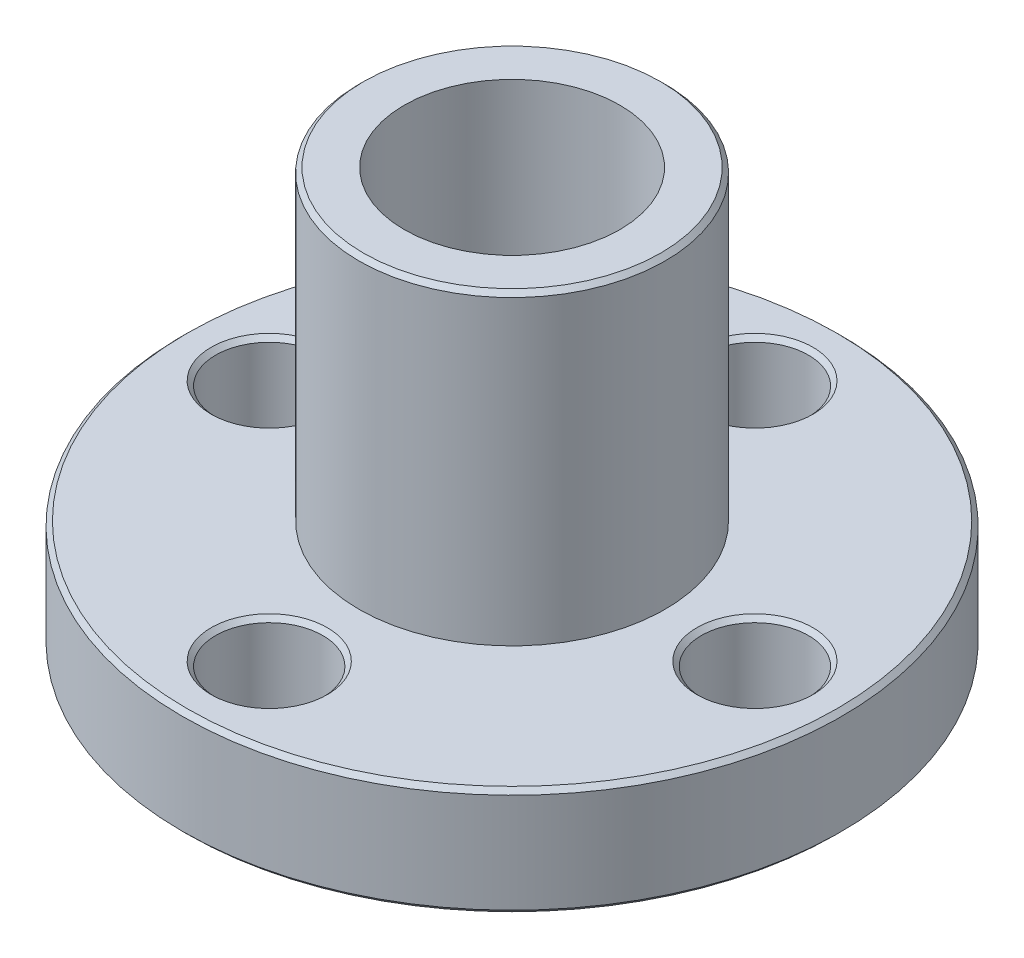
SolidWorks part; units mm, degrees
ref_plane "Alzado" through (0, 0, 0) normal (0, 0, 1) x (1, 0, 0)
ref_plane "Planta" through (0, 0, 0) normal (0, 1, 0) x (1, 0, 0)
ref_plane "Vista lateral" through (0, 0, 0) normal (1, 0, 0) x (0, 0, -1)
sketch "Croquis1" plane through (0, 0, 0) normal (0, 1, 0) x (1, 0, 0)
  circle A0 centre (0, 0) radius 10.925
  dimension "D1" = 21.85
extrude "Saliente-Extruir1" add sketch "Croquis1" along normal blind 3.6
sketch "Croquis2" plane through (0, 3.6, 0) normal (0, 1, 0) x (1, 0, 0)
  line L0 (-8.05, 0) -> (8.05, 0) construction
  line L1 (0, 8.05) -> (0, -8.05) construction
  circle A0 centre (-8.05, 0) radius 1.775
  circle A1 centre (8.05, 0) radius 1.775
  circle A2 centre (0, -8.05) radius 1.775
  circle A3 centre (0, 8.05) radius 1.775
  point P2 (0, 0)
  point P7 (0, 0)
  dimension "D2" = 3.55
  dimension "D1" = 16.1
extrude "Cortar-Extruir1" cut sketch "Croquis2" against normal blind 3.6
sketch "Croquis3" plane through (0, 3.6, 0) normal (0, 1, 0) x (1, 0, 0)
  circle A0 centre (0, 0) radius 5.075
  dimension "D1" = 10.15
extrude "Saliente-Extruir2" add sketch "Croquis3" along normal blind 10.15
sketch "Croquis4" plane through (0, 0, 0) normal (0, -1, 0) x (1, 0, 0)
  circle A0 centre (0, 0) radius 5.075
  dimension "D1" = 10.15
extrude "Saliente-Extruir3" add sketch "Croquis4" along normal blind 1.5
sketch "Croquis5" plane through (0, -1.5, 0) normal (0, -1, 0) x (1, 0, 0)
  circle A0 centre (0, 0) radius 3.575
  circle A1 centre (0, 0) radius 5.075 construction
  dimension "D1" = 1.5
extrude "Cortar-Extruir2" cut sketch "Croquis5" against normal blind 31.5
chamfer "Chaflán1" distance 0.15 angle 45 12 edges at (0, 13.75, 5.075) (0, 3.6, 10.925) (0, 0, 10.925) (0, -1.5, -5.075) (8.05, 3.6, 1.775) (0, 3.6, -6.275) (0, 3.6, 9.825) (-8.05, 3.6, 1.775) (8.05, 0, 1.775) (0, 0, -6.275) (-8.05, 0, 1.775) (0, 0, 9.825)
